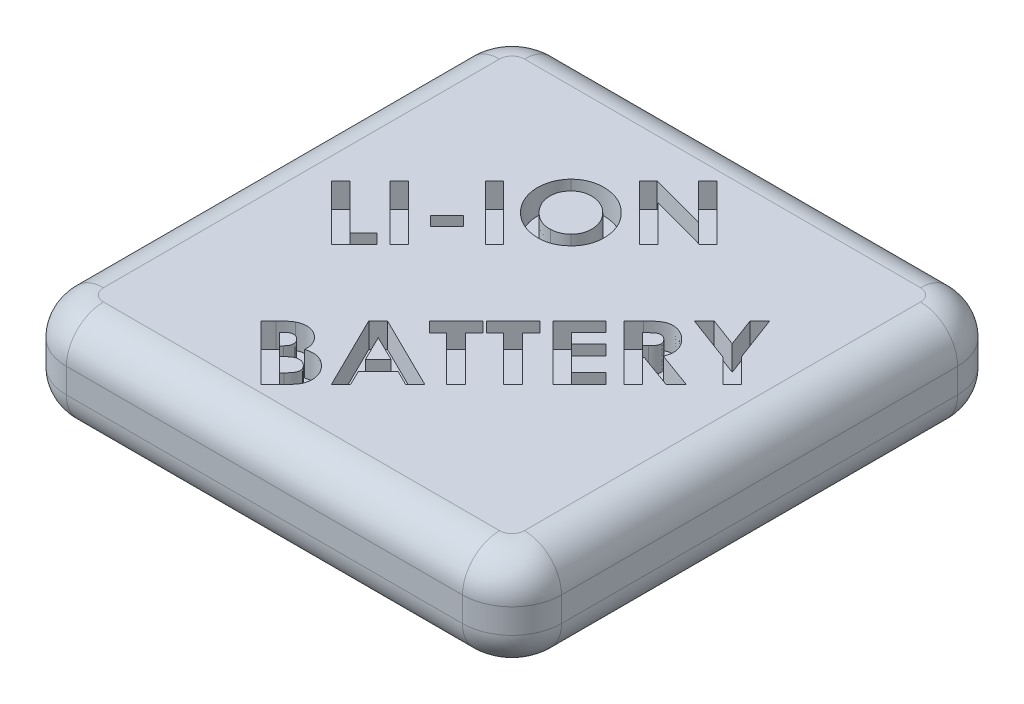
SolidWorks part; units mm, degrees
ref_plane "Front" through (0, 0, 0) normal (0, 0, 1) x (1, 0, 0)
ref_plane "Top" through (0, 0, 0) normal (0, 1, 0) x (1, 0, 0)
ref_plane "Right" through (0, 0, 0) normal (1, 0, 0) x (0, 0, -1)
sketch "Sketch1" plane through (0, 0, 0) normal (0, 1, 0) x (1, 0, 0)
  line L1 (-16, -20) -> (16, -20)
  line L2 (-20, -16) -> (-20, 16)
  line L3 (-16, 20) -> (16, 20)
  line L4 (20, -16) -> (20, 16)
  line L5 (-20, -20) -> (20, 20) construction
  line L6 (-20, 20) -> (20, -20) construction
  arc A0 (-16, -20) -> (-20, -16) centre (-16, -16) cw
  arc A1 (16, -20) -> (20, -16) centre (16, -16) ccw
  arc A2 (16, 20) -> (20, 16) centre (16, 16) cw
  arc A3 (-20, 16) -> (-16, 20) centre (-16, 16) cw
  point P0 (0, 0)
  dimension "D2" = 4
  dimension "D1" = 40
extrude "Boss-Extrude1" add sketch "Sketch1" along normal blind 8
fillet "Fillet1" radius 3 16 edges at (0, 0, 20) (18.8284, 0, 18.8284) (20, 0, 0) (18.8284, 0, -18.8284) (0, 0, -20) (-18.8284, 0, -18.8284) (-20, 0, 0) (-18.8284, 0, 18.8284) (-20, 8, 0) (-18.8284, 8, -18.8284) (0, 8, -20) (18.8284, 8, -18.8284) (20, 8, 0) (18.8284, 8, 18.8284) (0, 8, 20) (-18.8284, 8, 18.8284)
sketch "Sketch2" plane through (0, 8, 0) normal (0, 1, 0) x (1, 0, 0)
  line L0 (-16, -16) -> (16, 16) construction
  line L1 (-19.5355, -12.4645) -> (12.4645, 19.5355) construction
  arc A0 (-17, -16) -> (-16, -17) centre (-16, -16) ccw construction
  arc A1 (17, 16) -> (16, 17) centre (16, 16) ccw construction
  text T0 "<b>LI-ION</b>\r\n<b>BATTERY</b>" font "Century Gothic" height 6.35
  point P3 (0, 0)
  point P7 (0, 0)
  dimension "D1" = 5
extrude "Cut-Extrude2" cut sketch "Sketch2" against normal blind 2
